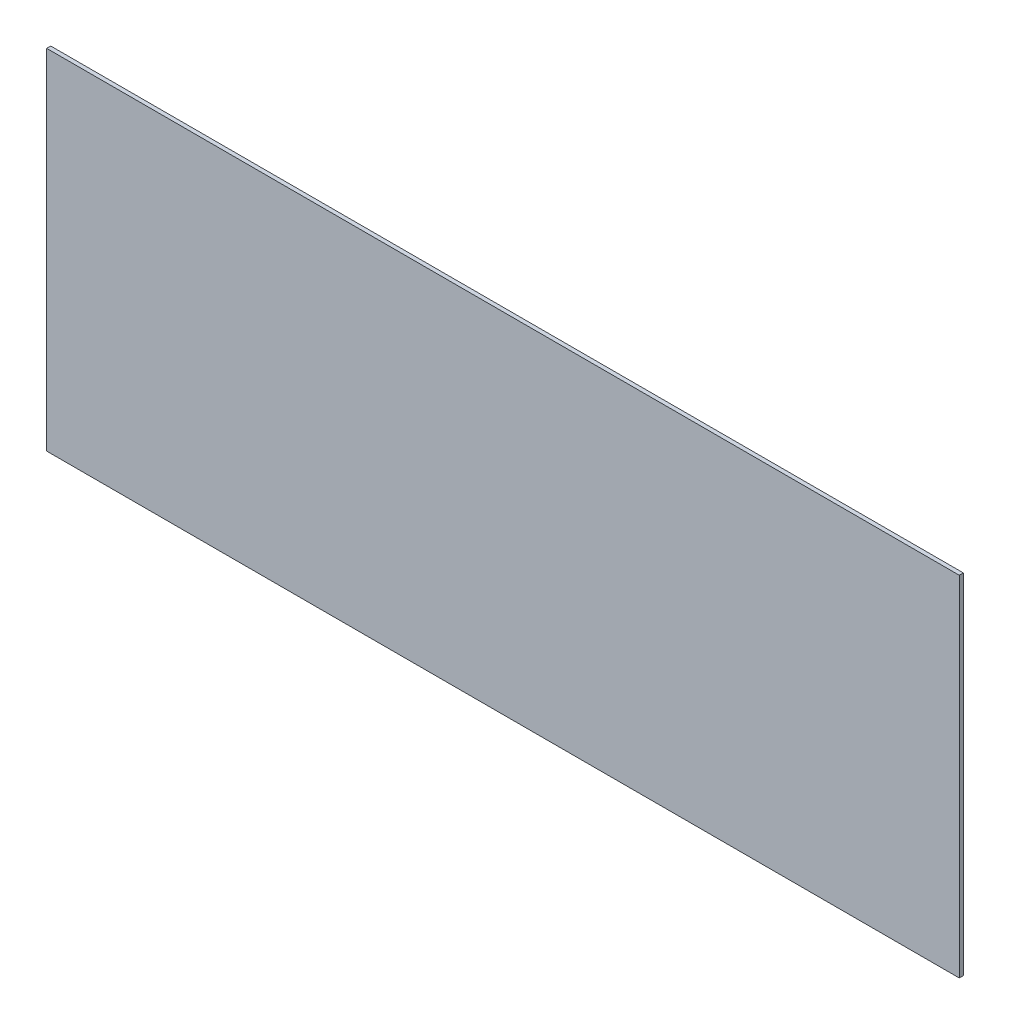
SolidWorks part; units mm, degrees
material "1345 Alloy"
ref_plane "Front Plane" through (0, 0, 0) normal (0, 0, 1) x (1, 0, 0)
ref_plane "Top Plane" through (0, 0, 0) normal (0, 1, 0) x (1, 0, 0)
ref_plane "Right Plane" through (0, 0, 0) normal (1, 0, 0) x (0, 0, -1)
sketch "Sketch1" plane through (0, 0, 0) normal (0, 0, 1) x (1, 0, 0)
  line L1 (-225, 86) -> (225, 86)
  line L2 (-225, 86) -> (-225, -86)
  line L3 (-225, -86) -> (225, -86)
  line L4 (225, 86) -> (225, -86)
  line L5 (-225, 86) -> (225, -86) construction
  line L6 (-225, -86) -> (225, 86) construction
  point P0 (0, 0)
  dimension "D1" = 450
  dimension "D2" = 172
extrude "Boss-Extrude1" add sketch "Sketch1" along normal blind 2
